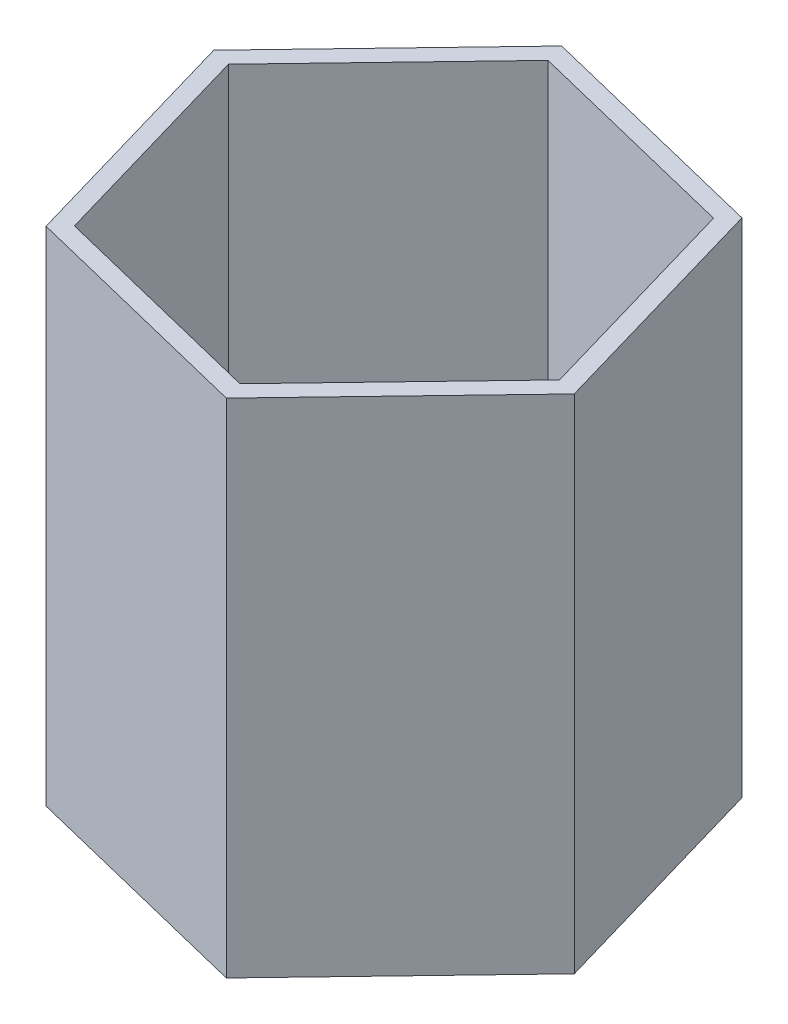
SolidWorks part; units mm, degrees
ref_plane "Front Plane" through (0, 0, 0) normal (0, 0, 1) x (1, 0, 0)
ref_plane "Top Plane" through (0, 0, 0) normal (0, 1, 0) x (1, 0, 0)
ref_plane "Right Plane" through (0, 0, 0) normal (1, 0, 0) x (0, 0, -1)
sketch "Sketch1" plane through (0, 0, 0) normal (0, 1, 0) x (1, 0, 0)
  line L1 (6.7835, 7.0727) -> (-2.7334, 9.4111)
  line L2 (-2.7334, 9.4111) -> (-9.5169, 2.3384)
  line L3 (-9.5169, 2.3384) -> (-6.7835, -7.0727)
  line L4 (-6.7835, -7.0727) -> (2.7334, -9.4111)
  line L5 (2.7334, -9.4111) -> (9.5169, -2.3384)
  line L6 (9.5169, -2.3384) -> (6.7835, 7.0727)
  line L7 (2.5103, -8.6428) -> (8.74, -2.1475)
  line L8 (8.74, -2.1475) -> (6.2298, 6.4954)
  line L9 (6.2298, 6.4954) -> (-2.5103, 8.6428)
  line L10 (-2.5103, 8.6428) -> (-8.74, 2.1475)
  line L11 (-8.74, 2.1475) -> (-6.2298, -6.4954)
  line L12 (-6.2298, -6.4954) -> (2.5103, -8.6428)
  circle A0 centre (0, 0) radius 8.487 construction
  circle A1 centre (0, 0) radius 7.7942 construction
  dimension "D1" = 9.8
  dimension "D2" = 9
extrude "Boss-Extrude1" add sketch "Sketch1" along normal blind 20
